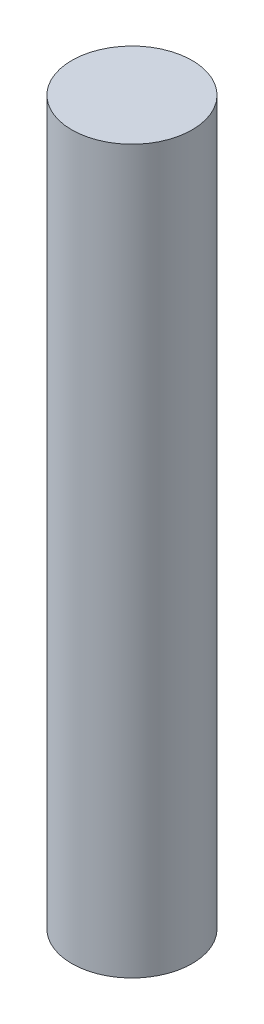
SolidWorks part; units mm, degrees
ref_plane "Front Plane" through (0, 0, 0) normal (0, 0, 1) x (1, 0, 0)
ref_plane "Top Plane" through (0, 0, 0) normal (0, 1, 0) x (1, 0, 0)
ref_plane "Right Plane" through (0, 0, 0) normal (1, 0, 0) x (0, 0, -1)
sketch "Sketch1" plane through (0, 0, 0) normal (0, 1, 0) x (1, 0, 0)
  circle A0 centre (0, 0) radius 25
extrude "Boss-Extrude1" add sketch "Sketch1" along normal blind 300
